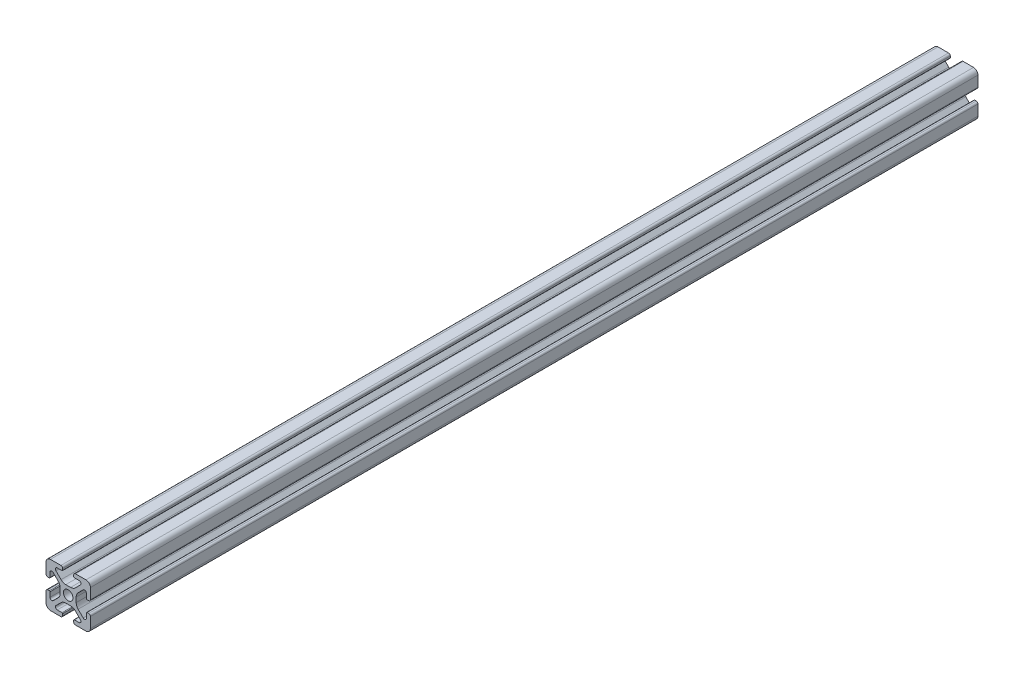
SolidWorks part; units mm, degrees
ref_plane "Front Plane" through (0, 0, 0) normal (0, 0, 1) x (1, 0, 0)
ref_plane "Top Plane" through (0, 0, 0) normal (0, 1, 0) x (1, 0, 0)
ref_plane "Right Plane" through (0, 0, 0) normal (1, 0, 0) x (0, 0, -1)
sketch "Sketch1" plane through (0, 0, 0) normal (0, 0, 1) x (1, 0, 0)
  line L0 (0, 10) -> (0, -10) construction
  line L1 (10, 0) -> (-10, 0) construction
  line L2 (-2.5, 10) -> (2.5, 10) construction
  line L3 (-5.75, 8.2) -> (5.75, 8.2) construction
  circle A0 centre (0, 0) radius 2.15 construction
  point P4 (0, 0)
  point P8 (0, 0)
  point P10 (0, 3.6)
  point P14 (0, 10)
  point P17 (0, 8.2)
  dimension "Thru Hole" = 4.3
  dimension "Height" = 20
  dimension "T Slot Depth" = 6.4
  dimension "T Slot Top Width" = 5
  dimension "T Slot Max Width" = 11.5
  dimension "Wall" = 1.8
sketch "Sketch2" plane through (0, 0, 0) normal (1, 0, 0) x (0, 0, -1)
  line L0 (200, 0) -> (-200, 0) construction
  point P4 (0, 0)
  dimension "D1" = 400
sketch "Sketch3" plane through (0, 0, 0) normal (0, 0, 1) x (1, 0, 0)
  line L0 (3.2874, 10) -> (8, 10)
  line L1 (10, 8) -> (10, -8) construction
  line L2 (8, -10) -> (-8, -10) construction
  line L3 (-10, 10) -> (10, -10) construction
  line L4 (2.5, 9.2126) -> (2.5, 8.5048)
  line L5 (-5.75, 8.2) -> (5.75, 8.2) construction
  line L6 (2.8048, 8.2) -> (4.9118, 8.2)
  line L7 (5.5045, 6.7691) -> (3.2141, 4.4787)
  line L8 (1.0928, 3.6) -> (-1.0928, 3.6)
  line L9 (0, 10) -> (0, -10) construction
  line L10 (5.75, 8.2) -> (5.75, 0) construction
  line L11 (10, 0) -> (-10, 0) construction
  line L12 (0, 0) -> (0, 10) construction
  line L13 (-2.5, 9.2126) -> (-2.5, 8.5048)
  line L14 (-5.5045, 6.7691) -> (-3.2141, 4.4787)
  line L15 (-2.8048, 8.2) -> (-4.9118, 8.2)
  line L16 (-3.2874, 10) -> (-8, 10)
  line L17 (0, 0) -> (-10, 0) construction
  line L18 (-10, 3.2874) -> (-10, 8)
  line L19 (-8.2, 2.8048) -> (-8.2, 4.9118)
  line L20 (-6.7691, 5.5045) -> (-4.4787, 3.2141)
  line L21 (-9.2126, 2.5) -> (-8.5048, 2.5)
  line L22 (-3.6, -1.0928) -> (-3.6, 1.0928)
  line L23 (-6.7691, -5.5045) -> (-4.4787, -3.2141)
  line L24 (-8.2, -2.8048) -> (-8.2, -4.9118)
  line L25 (-9.2126, -2.5) -> (-8.5048, -2.5)
  line L26 (-10, -3.2874) -> (-10, -8)
  line L27 (9.2126, -2.5) -> (8.5048, -2.5)
  line L28 (8.2, -2.8048) -> (8.2, -4.9118)
  line L29 (6.7691, -5.5045) -> (4.4787, -3.2141)
  line L30 (3.6, -1.0928) -> (3.6, 1.0928)
  line L31 (9.2126, 2.5) -> (8.5048, 2.5)
  line L32 (6.7691, 5.5045) -> (4.4787, 3.2141)
  line L33 (8.2, 2.8048) -> (8.2, 4.9118)
  line L34 (10, 8) -> (10, 3.2874)
  line L35 (10, -3.2874) -> (10, -8)
  line L36 (3.2874, -10) -> (8, -10)
  line L37 (-3.2874, -10) -> (-8, -10)
  line L38 (-6.7691, -5.5045) -> (-4.4787, -3.2141)
  line L39 (-2.8048, -8.2) -> (-4.9118, -8.2)
  line L40 (-5.5045, -6.7691) -> (-3.2141, -4.4787)
  line L41 (-2.5, -9.2126) -> (-2.5, -8.5048)
  line L42 (1.0928, -3.6) -> (-1.0928, -3.6)
  line L43 (5.5045, -6.7691) -> (3.2141, -4.4787)
  line L44 (2.8048, -8.2) -> (4.9118, -8.2)
  line L45 (2.5, -9.2126) -> (2.5, -8.5048)
  arc A0 (4.9118, 8.2) -> (5.5045, 6.7691) centre (4.9118, 7.3618) cw
  arc A1 (3.2141, 4.4787) -> (1.0928, 3.6) centre (1.0928, 6.6) cw
  circle A2 centre (0, 0) radius 2.15 construction
  circle A3 centre (0, 0) radius 2.15
  arc A4 (3.2874, 10) -> (2.5, 9.2126) centre (3.2874, 9.2126) ccw
  arc A5 (2.5, 8.5048) -> (2.8048, 8.2) centre (2.8048, 8.5048) ccw
  arc A6 (-3.2874, 10) -> (-2.5, 9.2126) centre (-3.2874, 9.2126) cw
  arc A7 (-4.9118, 8.2) -> (-5.5045, 6.7691) centre (-4.9118, 7.3618) ccw
  arc A8 (-3.2141, 4.4787) -> (-1.0928, 3.6) centre (-1.0928, 6.6) ccw
  arc A9 (-2.5, 8.5048) -> (-2.8048, 8.2) centre (-2.8048, 8.5048) cw
  arc A10 (-8.5048, 2.5) -> (-8.2, 2.8048) centre (-8.5048, 2.8048) ccw
  arc A11 (-4.4787, 3.2141) -> (-3.6, 1.0928) centre (-6.6, 1.0928) cw
  arc A12 (-8.2, 4.9118) -> (-6.7691, 5.5045) centre (-7.3618, 4.9118) cw
  arc A13 (-10, 3.2874) -> (-9.2126, 2.5) centre (-9.2126, 3.2874) ccw
  arc A14 (-8.5048, -2.5) -> (-8.2, -2.8048) centre (-8.5048, -2.8048) cw
  arc A15 (-10, -3.2874) -> (-9.2126, -2.5) centre (-9.2126, -3.2874) cw
  arc A16 (-4.4787, -3.2141) -> (-3.6, -1.0928) centre (-6.6, -1.0928) ccw
  arc A17 (-8.2, -4.9118) -> (-6.7691, -5.5045) centre (-7.3618, -4.9118) ccw
  arc A26 (-8, -10) -> (-10, -8) centre (-8, -8) cw
  arc A27 (-8, 10) -> (-10, 8) centre (-8, 8) ccw
  arc A28 (8, 10) -> (10, 8) centre (8, 8) cw
  arc A29 (10, -8) -> (8, -10) centre (8, -8) cw
  arc A30 (8.2, -4.9118) -> (6.7691, -5.5045) centre (7.3618, -4.9118) cw
  arc A31 (4.4787, -3.2141) -> (3.6, -1.0928) centre (6.6, -1.0928) cw
  arc A32 (10, -3.2874) -> (9.2126, -2.5) centre (9.2126, -3.2874) ccw
  arc A33 (8.5048, -2.5) -> (8.2, -2.8048) centre (8.5048, -2.8048) ccw
  arc A34 (10, 3.2874) -> (9.2126, 2.5) centre (9.2126, 3.2874) cw
  arc A35 (8.2, 4.9118) -> (6.7691, 5.5045) centre (7.3618, 4.9118) ccw
  arc A36 (4.4787, 3.2141) -> (3.6, 1.0928) centre (6.6, 1.0928) ccw
  arc A37 (8.5048, 2.5) -> (8.2, 2.8048) centre (8.5048, 2.8048) cw
  arc A38 (-2.5, -8.5048) -> (-2.8048, -8.2) centre (-2.8048, -8.5048) ccw
  arc A39 (-3.2141, -4.4787) -> (-1.0928, -3.6) centre (-1.0928, -6.6) cw
  arc A40 (-4.9118, -8.2) -> (-5.5045, -6.7691) centre (-4.9118, -7.3618) cw
  arc A41 (-3.2874, -10) -> (-2.5, -9.2126) centre (-3.2874, -9.2126) ccw
  arc A42 (2.5, -8.5048) -> (2.8048, -8.2) centre (2.8048, -8.5048) cw
  arc A43 (3.2874, -10) -> (2.5, -9.2126) centre (3.2874, -9.2126) cw
  arc A44 (3.2141, -4.4787) -> (1.0928, -3.6) centre (1.0928, -6.6) ccw
  arc A45 (4.9118, -8.2) -> (5.5045, -6.7691) centre (4.9118, -7.3618) ccw
  point P36 (2.5, 10)
  point P39 (2.5, 8.2)
  point P49 (0, 3.6)
  point P77 (-3.6, 0)
  point P78 (-8.2, -2.5)
  point P79 (-10, -2.5)
  point P104 (-10, -10)
  point P110 (10, 10)
  point P114 (10, -2.5)
  point P115 (8.2, -2.5)
  point P116 (3.6, 0)
  point P141 (0, -3.6)
  dimension "D1" = 3
  dimension "D2" = 0.8382
  dimension "D4" = 0.7874
  dimension "D5" = 0.3048
  dimension "D6" = 2
  dimension "D3" = 45
extrude "Boss-Extrude1" add sketch "Sketch3" along normal up to vertex (200 mm away) and the other way up to vertex (200 mm away) contours A45 L44 A42 L45 A43 L36 A29 L35 A32 L27 A33 L28 A30 L29 A31 L30 A36 L32 A35 L33 A37 L31 A34 L34 A28 L0 A4 L4 A5 L6 A0 L7 A1 L8 A8 L14 A7 L15 A9 L13 A6 L16 A27 L18 A13 L21 A10 L19 A12 L20 A11 up to point (0, 0, 200) other way up to point (0, 0, -200)
